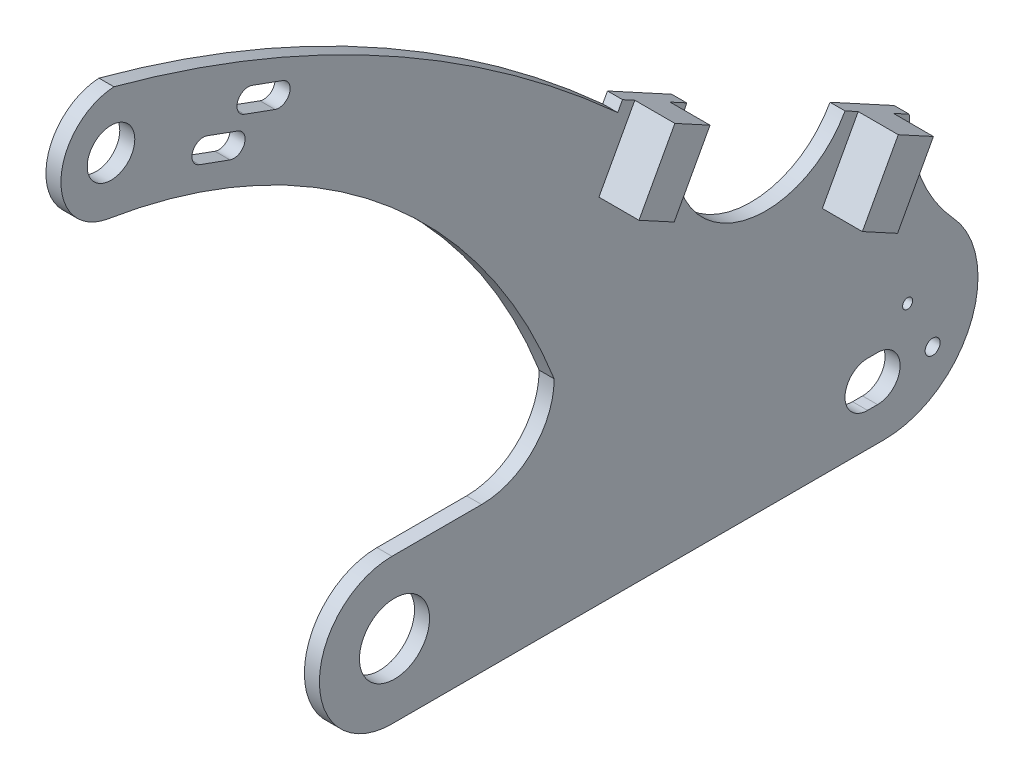
SolidWorks part; units mm, degrees
material "AISI 1020"
ref_plane "Front Plane" through (0, 0, 0) normal (0, 0, 1) x (1, 0, 0)
ref_plane "Top Plane" through (0, 0, 0) normal (0, 1, 0) x (1, 0, 0)
ref_plane "Right Plane" through (0, 0, 0) normal (1, 0, 0) x (0, 0, -1)
sketch "Sketch1" plane through (0, 0, 0) normal (1, 0, 0) x (0, 0, -1)
  line L0 (-49.1593, 0) -> (49.1593, 0)
  line L1 (49.1593, 37.5) -> (41.1593, 37.5) construction
  line L2 (-49.1593, 29) -> (-31.2593, 29)
  line L3 (0, -31.4761) -> (0, 31.4761) construction
  line L4 (-104.7059, 138) -> (-37.7059, 138) construction
  line L5 (32.1487, 42.1907) -> (-34.9377, 138) construction
  line L6 (45.8407, 11.2423) -> (47.8407, 11.2423) construction
  line L7 (45.8407, 15.7423) -> (47.8407, 15.7423)
  line L8 (45.8407, 6.7423) -> (47.8407, 6.7423)
  line L9 (-104.7059, 138) -> (-105.873, 115.7306) construction
  line L10 (-105.2895, 126.8653) -> (-115.2758, 127.3886) construction
  line L11 (-16.7593, 43.5) -> (-24.2593, 56.4904) construction
  line L12 (59.6251, 11.2423) -> (61.3276, 11.2423) construction
  line L13 (-49.478, 14.5) -> (-46.5284, 14.5) construction
  line L14 (-48.29, 14.5) -> (-46.0777, 14.5) construction
  line L15 (-86.8655, 118.0957) -> (-80.7575, 115.8726) construction
  line L16 (-86.096, 120.21) -> (-79.988, 117.9869)
  line L17 (-87.6351, 115.9814) -> (-81.5271, 113.7583)
  line L18 (-87.841, 113.2563) -> (-77.7033, 113.2563) construction
  line L19 (-77.8737, 122.3244) -> (-71.7657, 120.1012) construction
  line L20 (-77.1041, 124.4387) -> (-70.9961, 122.2155)
  line L21 (-78.6432, 120.21) -> (-72.5352, 117.9869)
  line L22 (-80.7575, 117.9869) -> (-78.616, 117.9869) construction
  line L23 (-72.7481, 117.9869) -> (-70.635, 117.9869) construction
  line L24 (41.3407, 60.8) -> (9.7153, 78) construction
  line L25 (9.7153, 78) -> (-3.1105, 84.9756)
  line L26 (41.3407, 60.8) -> (54.1665, 53.8244)
  line L28 (-3.1105, 84.9756) -> (-4.066, 83.2186)
  arc A3 (-49.1593, 0) -> (-49.1593, 29) centre (-49.1593, 14.5) cw
  arc A4 (62.9185, 31.4877) -> (49.1593, 0) centre (49.1593, 18.75) cw
  arc A5 (41.1593, 37.5) -> (32.1487, 42.1907) centre (41.1593, 48.5) cw construction
  arc A6 (32.1487, 42.1907) -> (25.3729, 51.4007) centre (-167.8609, -97.8576) ccw construction
  arc A7 (-16.7593, 43.5) -> (-31.2593, 29) centre (-31.2593, 43.5) cw
  arc A12 (-104.7059, 138) -> (-105.873, 115.7306) centre (-104.075, 126.8016) ccw
  arc A13 (-105.873, 115.7306) -> (-16.7593, 43.5) centre (-124.3727, 1.8199) cw
  circle A14 centre (58.8407, 11.2423) radius 1.5
  arc A15 (45.8407, 15.7423) -> (45.8407, 6.7423) centre (45.8407, 11.2423) ccw
  arc A16 (47.8407, 6.7423) -> (47.8407, 15.7423) centre (47.8407, 11.2423) ccw
  circle A17 centre (53.8407, 21.2423) radius 1
  circle A18 centre (-48.6593, 14.5) radius 7
  circle A19 centre (-105.2895, 126.8653) radius 4.75
  arc A20 (-86.096, 120.21) -> (-87.6351, 115.9814) centre (-86.8655, 118.0957) ccw
  arc A21 (-81.5271, 113.7583) -> (-79.988, 117.9869) centre (-80.7575, 115.8726) ccw
  arc A22 (-77.1041, 124.4387) -> (-78.6432, 120.21) centre (-77.8737, 122.3244) ccw
  arc A23 (-72.5352, 117.9869) -> (-70.9961, 122.2155) centre (-71.7657, 120.1012) ccw
  arc A24 (9.7153, 78) -> (41.3407, 60.8) centre (25.528, 69.4) ccw
  arc A25 (54.1665, 53.8244) -> (62.9185, 31.4877) centre (87.0463, 53.8244) ccw
  arc A26 (-4.066, 83.2186) -> (-104.7059, 138) centre (-167.8609, -97.8576) ccw
  point P2 (-63.6593, 14.5)
  point P3 (66.3407, 11.2423)
  point P5 (0, 0)
  point P14 (0, 0)
  point P26 (46.8407, 11.2423)
  point P34 (-115.2758, 127.3886)
  point P39 (41.3407, 11.2423)
  point P40 (52.3407, 11.2423)
  point P53 (-83.8115, 116.9842)
  point P60 (-88.9799, 118.8653)
  point P61 (-78.6432, 115.1031)
  point P64 (-74.8197, 121.2128)
  point P71 (-79.988, 123.0939)
  point P72 (-69.6514, 119.3317)
  point P77 (-75.5892, 119.0985)
  point P83 (-39.0841, 66.1895)
  dimension "D4" = 11
  dimension "D3" = 14.5
  dimension "D1" = 130
  dimension "D2" = 18.75
  dimension "D8" = 14.5
  dimension "D15" = 22.3
  dimension "D17" = 93
  dimension "D18" = 15
  dimension "D11" = 3
  dimension "D16" = 11
  dimension "D21" = 2
  dimension "D24" = 14
  dimension "D26" = 9.5
  dimension "D34" = 36
  dimension "D5" = 8
  dimension "D6" = 125
  dimension "D7" = 138
  dimension "D9" = 67
  dimension "D10" = 32.4
  dimension "D12" = 10
  dimension "D13" = 7.5
  dimension "D14" = 14.5
  dimension "D19" = 9
  dimension "D20" = 14
  dimension "D22" = 12.5
  dimension "D23" = 10
  dimension "D25" = 15
  dimension "D27" = 11
  dimension "D28" = 4.5
  dimension "D29" = 20
  dimension "D30" = 16.3096
  dimension "D31" = 8
  dimension "D32" = 11
  dimension "D33" = 4.5
  dimension "D35" = 60.8
  dimension "D36" = 78
  dimension "D37" = 14.6
  dimension "D38" = 2
extrude "Boss-Extrude1" add sketch "Sketch1" along normal blind 3
sketch "Sketch2" plane through (3, 0, 0) normal (1, 0, 0) x (0, 0, -1)
  line L0 (54.1665, 53.8244) -> (41.3407, 60.8) construction
  line L1 (43.9761, 59.3667) -> (51.0039, 55.5444)
  line L2 (43.9761, 59.3667) -> (36.8094, 46.1895)
  line L3 (36.8094, 46.1895) -> (43.8373, 42.3672)
  line L4 (51.0039, 55.5444) -> (43.8373, 42.3672)
  line L5 (9.7153, 78) -> (-3.1105, 84.9756) construction
  line L6 (-0.6507, 83.6378) -> (6.3771, 79.8156)
  line L7 (-0.6507, 83.6378) -> (-7.8174, 70.4606)
  line L8 (-7.8174, 70.4606) -> (-0.7895, 66.6383)
  line L9 (6.3771, 79.8156) -> (-0.7895, 66.6383)
  arc A0 (9.7153, 78) -> (41.3407, 60.8) centre (25.528, 69.4) ccw construction
  arc A1 (9.7153, 78) -> (41.3407, 60.8) centre (25.528, 69.4) ccw construction
  point P15 (0, 0)
  dimension "D1" = 8
  dimension "D2" = 15
  dimension "D3" = 3
  dimension "D4" = 3.8
extrude "Boss-Extrude2" add sketch "Sketch2" along normal blind 8
